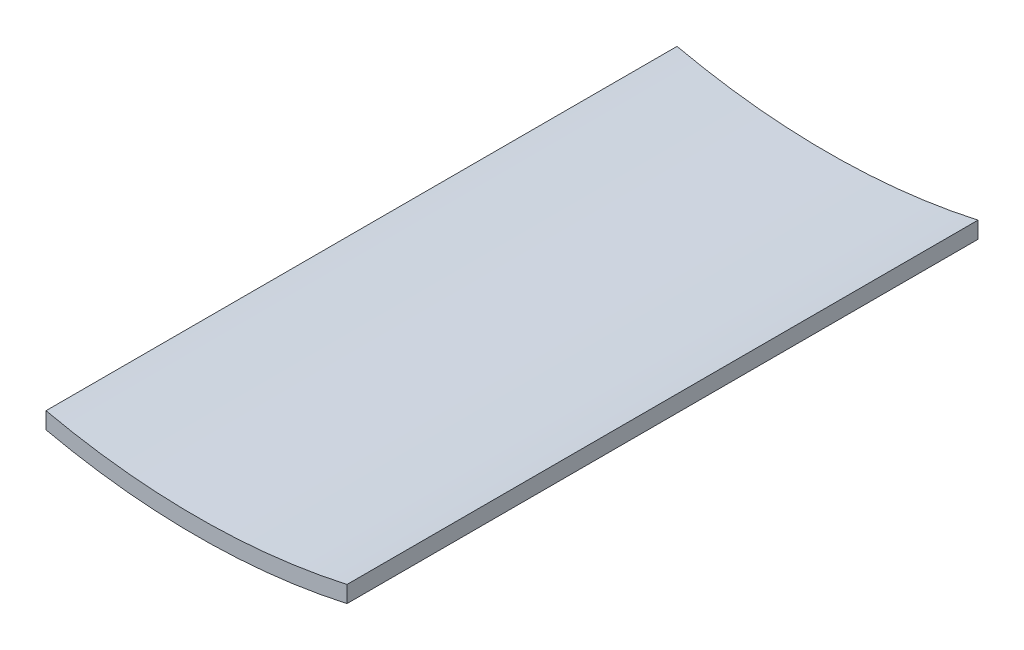
SolidWorks part; units mm, degrees
material "Maple"
ref_plane "Front Plane" through (0, 0, 0) normal (0, 0, 1) x (1, 0, 0)
ref_plane "Top Plane" through (0, 0, 0) normal (0, 1, 0) x (1, 0, 0)
ref_plane "Right Plane" through (0, 0, 0) normal (1, 0, 0) x (0, 0, -1)
sketch "Sketch1" plane through (0, 0, 0) normal (0, 0, 1) x (1, 0, 0)
  line L0 (0, 0) -> (230.1875, 0)
  line L1 (115.0937, 0) -> (115.0937, -12.7)
  line L2 (230.1875, 0) -> (230.1875, -12.7)
  line L3 (0, 0) -> (0, -12.7)
  arc A0 (230.1875, 0) -> (0, 0) centre (115.0938, 515.1686) cw
  arc A1 (230.1875, -12.7) -> (0, -12.7) centre (115.0938, 502.4686) cw
  point P6 (115.0937, -12.7)
  dimension "D1" = 2
extrude "Boss-Extrude1" add sketch "Sketch1" along normal blind 482.6 contours A1 L2 A0 L3
